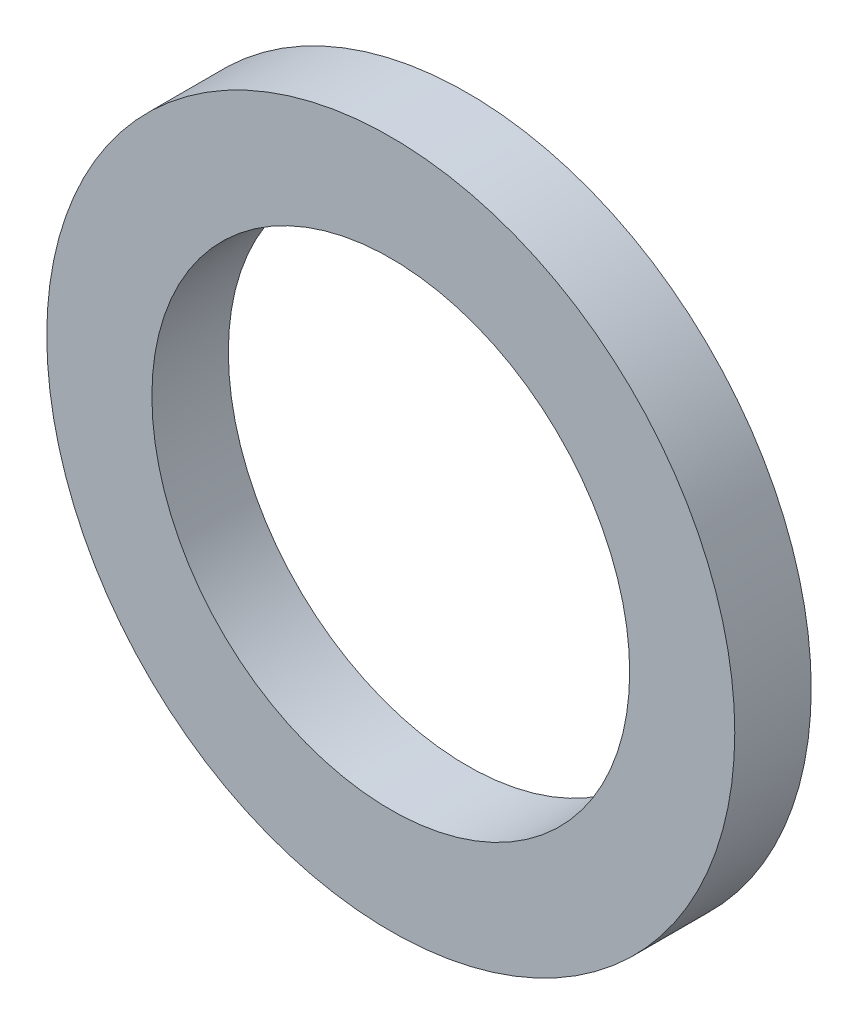
SolidWorks part; units mm, degrees
ref_plane "前视基准面" through (0, 0, 0) normal (0, 0, 1) x (1, 0, 0)
ref_plane "上视基准面" through (0, 0, 0) normal (0, 1, 0) x (1, 0, 0)
ref_plane "右视基准面" through (0, 0, 0) normal (1, 0, 0) x (0, 0, -1)
sketch "草图1" plane through (0, 0, 0) normal (0, 0, 1) x (1, 0, 0)
  circle A0 centre (0, 0) radius 25
  circle A1 centre (0, 0) radius 36
  dimension "D1" = 50
  dimension "D2" = 72
extrude "凸台-拉伸1" add sketch "草图1" along normal blind 8
